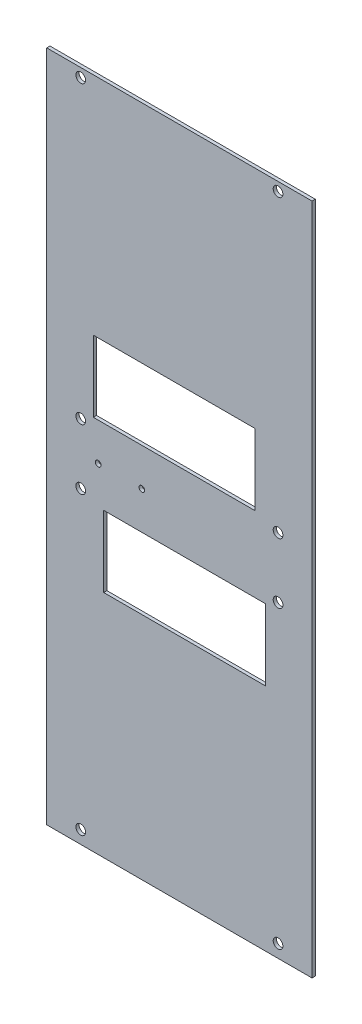
SolidWorks part; units mm, degrees
material "CFRP"
ref_plane "Front Plane" through (0, 0, 0) normal (0, 0, 1) x (1, 0, 0)
ref_plane "Top Plane" through (0, 0, 0) normal (0, 1, 0) x (1, 0, 0)
ref_plane "Right Plane" through (0, 0, 0) normal (1, 0, 0) x (0, 0, -1)
sketch "Sketch1" plane through (0, 0, 0) normal (0, 0, 1) x (1, 0, 0)
  line L1 (41.6, -104) -> (-41.6, -104)
  line L2 (41.6, -104) -> (41.6, 104)
  line L3 (41.6, 104) -> (-41.6, 104)
  line L4 (-41.6, -104) -> (-41.6, 104)
  line L5 (41.6, -104) -> (-41.6, 104) construction
  line L6 (41.6, 104) -> (-41.6, -104) construction
  point P0 (0, 0)
  dimension "D1" = 83.2
  dimension "D2" = 208
extrude "Boss-Extrude1" add sketch "Sketch1" along normal blind 1
hole_wizard "Ø3.0 (3) Diameter Hole1" positions "Sketch3" profile "Sketch2" hole size "Ø3.0" standard "ANSI Metric"
sketch "Sketch3" plane through (0, 0, 1) normal (0, 0, 1) x (1, 0, 0)
  line L6 (-41.6, -104) -> (41.6, -104) construction
  line L9 (41.6, 104) -> (-41.6, 104) construction
  line L10 (0, 104) -> (0, 163.7587) construction
  line L11 (0, 104) -> (0, -152.1509) construction
  point P0 (-30.5, 10)
  point P2 (30.5, 10)
  point P15 (30.5, -100)
  point P17 (-30.5, -100)
  point P54 (-30.5, 101.3)
  point P56 (30.5, 101.3)
  point P58 (-30.5, -8.7)
  point P60 (30.5, -8.7)
  dimension "D2" = 4
  dimension "D3" = 2.7
  dimension "D4" = 4
  dimension "D5" = 30.5
  dimension "D6" = 30.5
  dimension "D7" = 94
  dimension "D8" = 30.5
  dimension "D9" = 2.7
  dimension "D10" = 94
  dimension "D11" = 30.5
  dimension "D12" = 30.5
  dimension "D13" = 30.5
  dimension "D14" = 30.5
  dimension "D15" = 30.5
  dimension "D16" = 112.7
  dimension "D17" = 112.7
sketch "Sketch2" plane through (-30.5, 10, 1) normal (1, 0, 0) x (0, -1, 0)
  line L0 (0, 0) -> (0, 1)
  line L1 (0, 1) -> (1.5, 1)
  line L2 (1.5, 1) -> (1.5, 0)
  line L5 (1.5, 0) -> (0, 0)
  line L10 (0, 1) -> (-1.5, 1) construction
  line L11 (0, -6.35) -> (0, 107.95) construction
  dimension "Hole Dia." = 3
  dimension "Hole Depth" = 1
  dimension "Drill Angle" = 180
sketch "Sketch4" plane through (0, 0, 1) normal (0, 0, 1) x (1, 0, 0)
  line L0 (-41.6, 104) -> (-41.6, -104) construction
  line L1 (-23.4, -33) -> (26.6, -33)
  line L2 (-23.4, -33) -> (-23.4, -11)
  line L3 (-23.4, -11) -> (26.6, -11)
  line L4 (26.6, -33) -> (26.6, -11)
  line L5 (41.6, 104) -> (-41.6, 104) construction
  line L7 (23.4, 34.3) -> (-26.6, 34.3)
  line L8 (23.4, 34.3) -> (23.4, 12.3)
  line L9 (23.4, 12.3) -> (-26.6, 12.3)
  line L10 (-26.6, 34.3) -> (-26.6, 12.3)
  line L11 (-41.6, -104) -> (41.6, -104) construction
  line L12 (41.6, -104) -> (41.6, 104) construction
  dimension "D1" = 22
  dimension "D2" = 50
  dimension "D3" = 71
  dimension "D4" = 15
  dimension "D5" = 50
  dimension "D6" = 22
  dimension "D7" = 15
  dimension "D8" = 69.7
extrude "Cut-Extrude1" cut sketch "Sketch4" against normal blind 10
hole_wizard "Ø1.75 (1.75) Diameter Hole1" positions "Sketch6" profile "Sketch5" hole size "Ø1.75" standard "ANSI Metric" end condition through all
sketch "Sketch6" plane through (0, 0, 1) normal (0, 0, 1) x (1, 0, 0)
  point P0 (-25.1, 0.65)
  point P3 (-11.6, 0.65)
sketch "Sketch5" plane through (-25.1, 0.65, 1) normal (1, 0, 0) x (0, -1, 0)
  line L0 (0, 0) -> (0, 1)
  line L1 (0, 1) -> (0.875, 1)
  line L2 (0.875, 1) -> (0.875, 0)
  line L5 (0.875, 0) -> (0, 0)
  line L11 (0, -6.35) -> (0, 107.95) construction
  dimension "Thru Hole Dia." = 1.75
  dimension "Thru Hole Depth" = 1
sketch "Sketch7" plane through (0, 0, 1) normal (0, 0, 1) x (1, 0, 0)
  line L0 (41.6, 104) -> (-41.6, 104) construction
  line L1 (41, -104) -> (-41, -104)
  line L2 (41, -104) -> (41, 104)
  line L3 (41, 104) -> (-41, 104)
  line L4 (-41, -104) -> (-41, 104)
  line L5 (41, -104) -> (-41, 104) construction
  line L6 (41, 104) -> (-41, -104) construction
  line L8 (64.5102, -126.4044) -> (-64.5102, -126.4044)
  line L9 (64.5102, -126.4044) -> (64.5102, 126.4044)
  line L10 (64.5102, 126.4044) -> (-64.5102, 126.4044)
  line L11 (-64.5102, -126.4044) -> (-64.5102, 126.4044)
  line L12 (64.5102, -126.4044) -> (-64.5102, 126.4044) construction
  line L13 (64.5102, 126.4044) -> (-64.5102, -126.4044) construction
  point P0 (0, 0)
  point P8 (0, 0)
  dimension "D1" = 82
extrude "Cut-Extrude2" cut sketch "Sketch7" against normal blind 10
